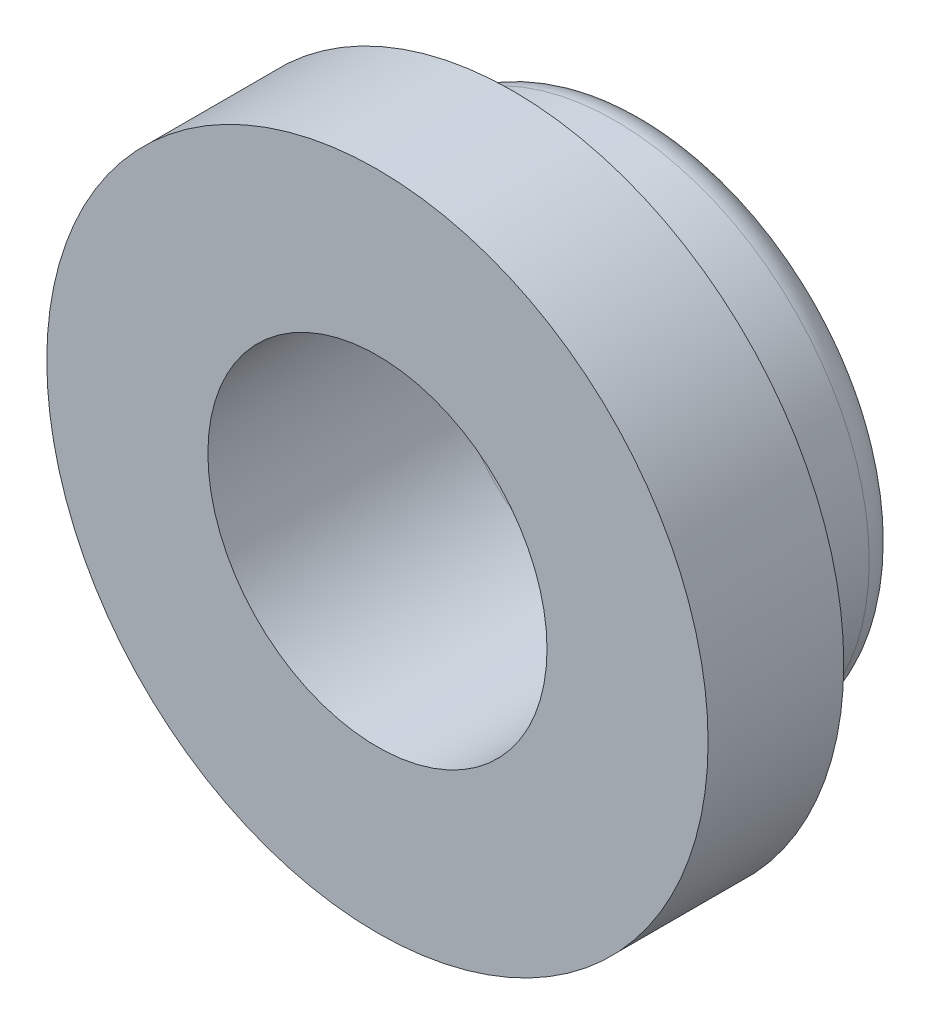
SolidWorks part; units mm, degrees
ref_plane "Plan de face" through (0, 0, 0) normal (0, 0, 1) x (1, 0, 0)
ref_plane "Plan de dessus" through (0, 0, 0) normal (0, 1, 0) x (1, 0, 0)
ref_plane "Plan de droite" through (0, 0, 0) normal (1, 0, 0) x (0, 0, -1)
sketch "Sketch1" plane through (0, 0, 0) normal (0, 0, 1) x (1, 0, 0)
  circle A0 centre (0, 0) radius 3.75
  dimension "D1" = 7.5
extrude "Boss-Extrude1" add sketch "Sketch1" along normal blind 4
sketch "Sketch3" plane through (0, 0, 4) normal (0, 0, 1) x (1, 0, 0)
  circle A0 centre (0, 0) radius 4.875
  dimension "D1" = 9.75
extrude "Boss-Extrude2" add sketch "Sketch3" against normal blind 2
sketch "Sketch4" plane through (0, 0, 4) normal (0, 0, 1) x (1, 0, 0)
  circle A0 centre (0, 0) radius 2.5
  dimension "D1" = 5
extrude "Cut-Extrude1" cut sketch "Sketch4" against normal through all
fillet "Fillet1" radius 0.5 2 edges at (2.5, 0, 0) (3.75, 0, 0)
